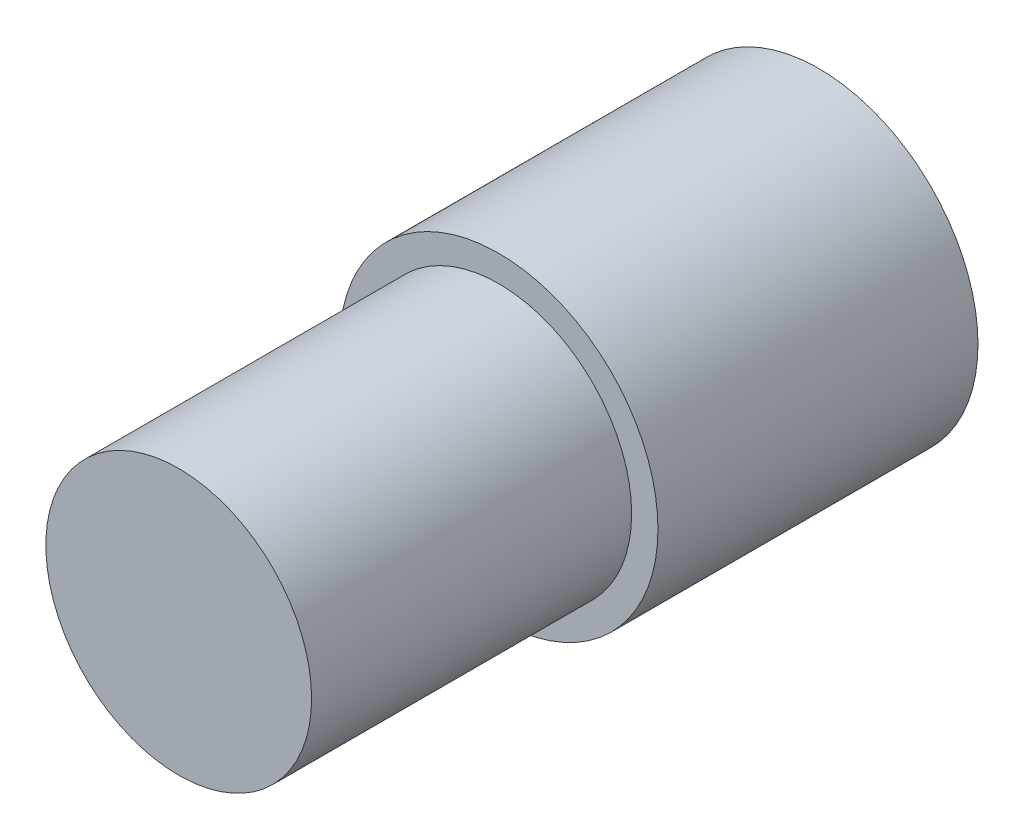
SolidWorks part; units mm, degrees
ref_plane "Front Plane" through (0, 0, 0) normal (0, 0, 1) x (1, 0, 0)
ref_plane "Top Plane" through (0, 0, 0) normal (0, 1, 0) x (1, 0, 0)
ref_plane "Right Plane" through (0, 0, 0) normal (1, 0, 0) x (0, 0, -1)
sketch "Sketch1" plane through (0, 0, 0) normal (0, 0, 1) x (1, 0, 0)
  circle A0 centre (0, 0) radius 4.975
  dimension "D1" = 9.95
extrude "Boss-Extrude1" add sketch "Sketch1" along normal blind 10
sketch "Sketch2" plane through (0, 0, 10) normal (0, 0, 1) x (1, 0, 0)
  circle A0 centre (0, 0) radius 4.152
extrude "Boss-Extrude2" add sketch "Sketch2" along normal blind 10
